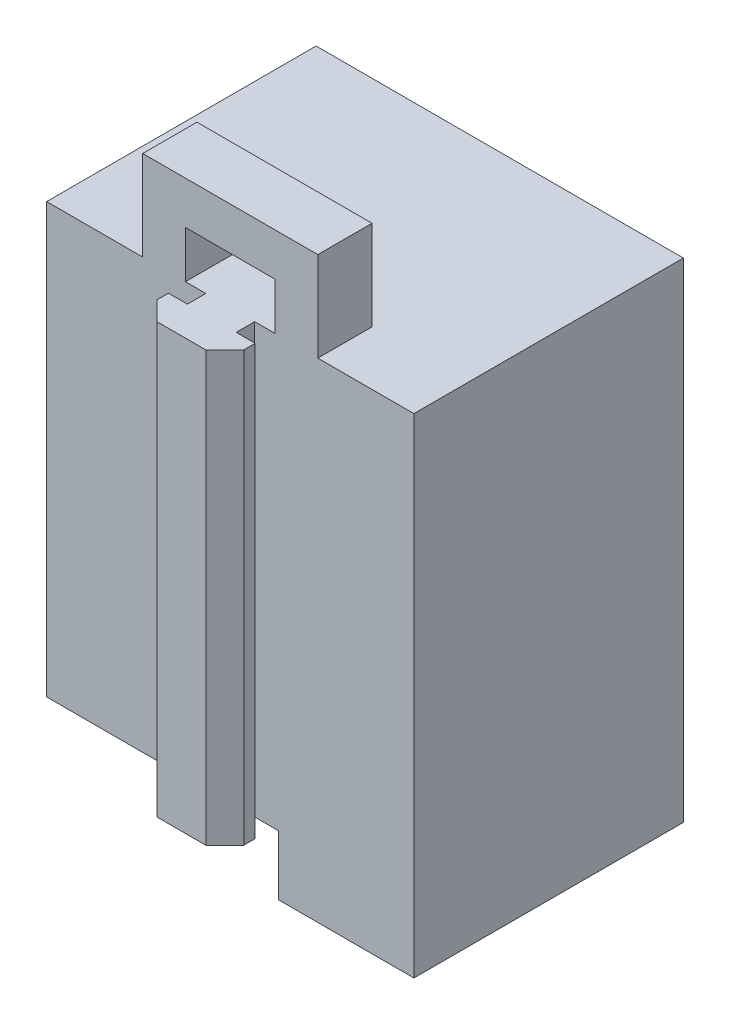
SolidWorks part; units mm, degrees
ref_plane "Front Plane" through (0, 0, 0) normal (0, 0, 1) x (1, 0, 0)
ref_plane "Top Plane" through (0, 0, 0) normal (0, 1, 0) x (1, 0, 0)
ref_plane "Right Plane" through (0, 0, 0) normal (1, 0, 0) x (0, 0, -1)
sketch "Sketch1" plane through (0, 0, 0) normal (0, 0, 1) x (1, 0, 0)
  line L0 (-16, -31.228) -> (-16, 15) construction
  line L1 (-16.5, 15.5) -> (16.5, 15.5)
  line L2 (-16.5, 15.5) -> (-16.5, -29.728)
  line L4 (16.5, 15.5) -> (16.5, -28.3998)
  line L7 (11.67, -31.728) -> (16.5, -31.728)
  line L8 (16.5, -28.3998) -> (16.5, -31.728)
  line L9 (-21.5, 20.5) -> (21.5, 20.5)
  line L10 (-21.5, 20.5) -> (-21.5, -29.728)
  line L11 (11.67, -36.728) -> (21.5, -36.728)
  line L12 (21.5, 20.5) -> (21.5, -36.728)
  line L14 (11.67, -36.728) -> (11.67, -29.728)
  line L15 (11.67, -29.728) -> (-21.5, -29.728)
  line L16 (16, -31.228) -> (16, 15) construction
  line L17 (16, 15) -> (-16, 15) construction
  line L18 (-5.8837, -31.228) -> (-16, -31.228) construction
  line L19 (9.67, -62.028) -> (9.67, -31.228) construction
  line L20 (16, -31.228) -> (0.8237, -31.228) construction
  point P4 (8.3745, -28.3998)
  point P19 (0, 20.5)
  point P20 (0, 0)
  point P21 (0, 0)
  point P24 (11.2356, -38.227)
  point P27 (14.085, -31.728)
  dimension "D1" = 0.5
  dimension "D2" = 0.5
  dimension "D3" = 0.5
  dimension "D4" = 5
  dimension "D5" = 5
  dimension "D6" = 5
  dimension "D7" = 1.5
  dimension "D8" = 2
  dimension "D9" = 5
  dimension "D10" = 0.5
extrude "Boss-Extrude1" add sketch "Sketch1" against normal up to surface (25.2 mm away) contours L15 L2 L1 L4 L8 L7 L14 L11 L12 L9 L10
sketch "Sketch2" plane through (0, 0, 0) normal (0, 0, 1) x (1, 0, 0)
  line L0 (21.5, 20.5) -> (21.5, -36.728) construction
  line L1 (-21.5, 20.5) -> (21.5, 20.5)
  line L2 (-21.5, 20.5) -> (-21.5, -29.728)
  line L3 (-21.5, -29.728) -> (11.67, -29.728)
  line L4 (21.5, 20.5) -> (21.5, -29.728)
  line L5 (11.67, -36.728) -> (21.5, -36.728) construction
  line L6 (11.67, -36.728) -> (21.5, -36.728)
  line L7 (11.67, -36.728) -> (11.67, -29.728)
  line L9 (21.5, -36.728) -> (21.5, -29.728)
  line L10 (-16.5, -29.728) -> (-21.5, -29.728) construction
  line L11 (11.67, -36.728) -> (11.67, -31.728) construction
extrude "Boss-Extrude2" add sketch "Sketch2" along normal blind 6.35
sketch "Sketch3" plane through (0, -29.728, 0) normal (0, -1, 0) x (1, 0, 0)
  line L5 (-16.5, 0) -> (11.67, 0) construction
  line L7 (-21.5, 6.35) -> (11.67, 6.35) construction
  line L9 (11.67, 6.35) -> (5.67, 6.35)
  line L10 (5.67, 6.35) -> (5.67, 0)
  line L11 (5.67, 0) -> (11.67, -6)
  line L12 (11.67, -25.2) -> (11.67, 6.35) construction
  line L13 (11.67, -6) -> (11.67, 6.35)
  dimension "D1" = 45
  dimension "D2" = 6
extrude "Boss-Extrude3" add sketch "Sketch3" along normal up to surface (5 mm away) from surface
sketch "Sketch4" plane through (0, 0, 6.35) normal (0, 0, 1) x (1, 0, 0)
  line L0 (21.5, 20.5) -> (-21.5, 20.5) construction
  line L1 (5.67, -31.728) -> (11.67, -31.728)
  line L2 (5.67, -31.728) -> (5.67, -29.728)
  line L3 (5.67, -29.728) -> (11.67, -29.728)
  line L4 (11.67, -31.728) -> (11.67, -29.728)
  line L5 (-5.25, 20.5) -> (5.25, 20.5)
  line L6 (-5.25, 20.5) -> (-5.25, 26)
  line L7 (-5.25, 26) -> (5.25, 26)
  line L8 (5.25, 20.5) -> (5.25, 26)
  line L10 (-10.25, 20.5) -> (10.25, 20.5)
  line L11 (-10.25, 20.5) -> (-10.25, 31)
  line L12 (-10.25, 31) -> (10.25, 31)
  line L13 (10.25, 20.5) -> (10.25, 31)
  arc A0 (-1.833, 2.5) -> (1.833, 2.5) centre (0, 0) ccw construction
  arc A1 (-1.833, 2.5) -> (1.833, 2.5) centre (0, 0) ccw
  point P16 (-5.25, 23.25)
  point P20 (0, 20.5)
  line M2 (-21.5, -29.728) -> (11.67, -29.728)
  line M3 (11.67, -29.728) -> (11.67, -31.728)
  line M4 (11.67, -31.728) -> (5.67, -31.728)
  line M8 (21.5, 20.5) -> (-21.5, 20.5)
  dimension "D1" = 5.5
  dimension "D2" = 10.5
  dimension "D3" = 5
  dimension "D4" = 5
  dimension "D5" = 5
extrude "Boss-Extrude4" add sketch "Sketch4" against normal up to surface (6.35 mm away) contours L13 L12 L11 L6 L7 L8 M8 | L2 M4 M3 M2 up to face at (3.89, -15.3187, 0)
sketch "Sketch5" plane through (0, 20.5, 0) normal (0, 1, 0) x (1, 0, 0)
  line L0 (-2.86, -6.35) -> (-2.86, -8.51)
  line L1 (-10.25, -6.35) -> (10.25, -6.35) construction
  line L2 (-2.86, -8.51) -> (-5.08, -8.51)
  line L3 (-5.08, -8.51) -> (-5.08, -9.85)
  line L4 (-5.08, -9.85) -> (-2.86, -12.07)
  line L5 (-2.86, -12.07) -> (2.86, -12.07)
  line L6 (2.86, -12.07) -> (5.08, -9.85)
  line L7 (5.08, -9.85) -> (5.08, -8.51)
  line L8 (5.08, -8.51) -> (2.86, -8.51)
  line L9 (2.86, -8.51) -> (2.86, -6.35)
  line L10 (2.86, -6.35) -> (-2.86, -6.35)
  point P12 (-5.08, -9.18)
  point P13 (0, 0)
  point P14 (0, 0)
  point P15 (0, -6.35)
  dimension "D1" = 2.16
  dimension "D2" = 5.72
  dimension "D3" = 5.72
  dimension "D4" = 10.16
extrude "Boss-Extrude5" add sketch "Sketch5" against normal up to surface (50.228 mm away) up to face at (-10.7767, -29.728, -6.2833)
